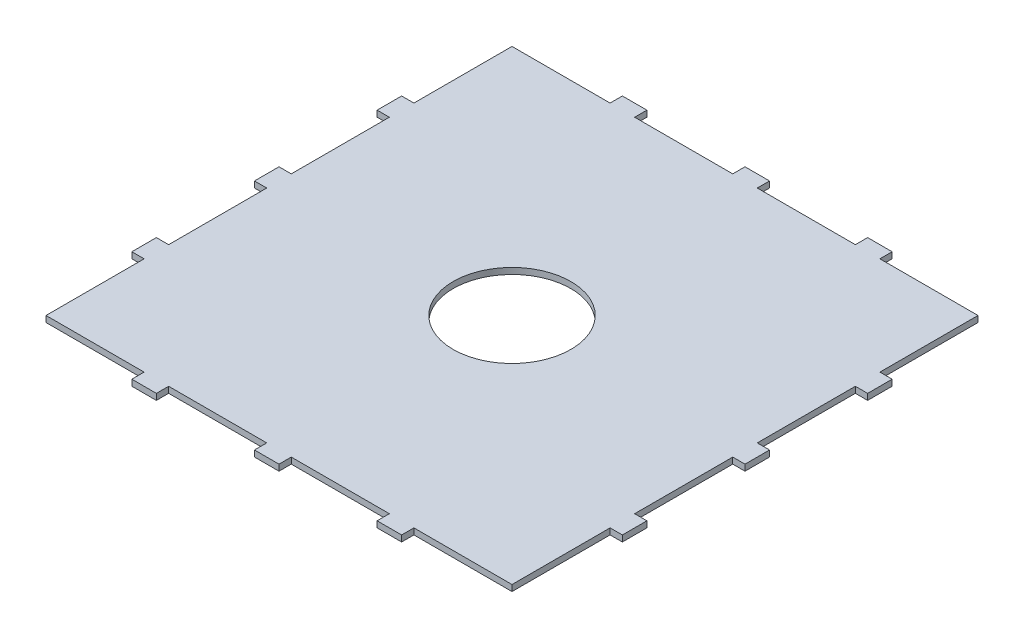
SolidWorks part; units mm, degrees
material "6061 Alloy"
ref_plane "Front Plane" through (0, 0, 0) normal (0, 0, 1) x (1, 0, 0)
ref_plane "Top Plane" through (0, 0, 0) normal (0, 1, 0) x (1, 0, 0)
ref_plane "Right Plane" through (0, 0, 0) normal (1, 0, 0) x (0, 0, -1)
sketch "Sketch1" plane through (0, 0, 0) normal (0, 1, 0) x (1, 0, 0)
  line L0 (0, 63.5) -> (0, -63.5) construction
  line L1 (63.5, -63.5) -> (-63.5, -63.5) construction
  line L2 (63.5, -63.5) -> (63.5, 63.5) construction
  line L3 (63.5, 63.5) -> (-63.5, 63.5) construction
  line L4 (-63.5, -63.5) -> (-63.5, 63.5) construction
  line L5 (63.5, -63.5) -> (-63.5, 63.5) construction
  line L6 (63.5, 63.5) -> (-63.5, -63.5) construction
  line L7 (-63.5, 0) -> (63.5, 0) construction
  line L8 (3.175, 63.5) -> (-3.175, 63.5)
  line L9 (-3.175, 63.5) -> (-3.175, 60.325)
  line L10 (-3.175, 60.325) -> (-28.575, 60.325)
  line L11 (-28.575, 60.325) -> (-28.575, 63.5)
  line L12 (-28.575, 63.5) -> (-34.925, 63.5)
  line L13 (-34.925, 63.5) -> (-34.925, 60.325)
  line L14 (-34.925, 60.325) -> (-60.325, 60.325)
  line L15 (-60.325, 60.325) -> (-60.325, 34.925)
  line L16 (-60.325, 34.925) -> (-63.5, 34.925)
  line L17 (-63.5, 34.925) -> (-63.5, 28.575)
  line L18 (-63.5, 28.575) -> (-60.325, 28.575)
  line L19 (-60.325, 28.575) -> (-60.325, 3.175)
  line L20 (-60.325, 3.175) -> (-63.5, 3.175)
  line L21 (-63.5, 3.175) -> (-63.5, -3.175)
  line L22 (-63.5, -28.575) -> (-60.325, -28.575)
  line L23 (-63.5, -34.925) -> (-63.5, -28.575)
  line L24 (-60.325, -34.925) -> (-63.5, -34.925)
  line L25 (-60.325, -60.325) -> (-60.325, -34.925)
  line L26 (-34.925, -60.325) -> (-60.325, -60.325)
  line L27 (-34.925, -63.5) -> (-34.925, -60.325)
  line L28 (-28.575, -63.5) -> (-34.925, -63.5)
  line L29 (-28.575, -60.325) -> (-28.575, -63.5)
  line L30 (-3.175, -60.325) -> (-28.575, -60.325)
  line L31 (-3.175, -63.5) -> (-3.175, -60.325)
  line L32 (3.175, -63.5) -> (-3.175, -63.5)
  line L33 (-60.325, -28.575) -> (-60.325, -3.175)
  line L34 (-60.325, -3.175) -> (-63.5, -3.175)
  line L35 (63.5, -63.5) -> (63.5, 63.5) construction
  line L36 (60.325, -3.175) -> (63.5, -3.175)
  line L37 (60.325, -28.575) -> (60.325, -3.175)
  line L38 (3.175, -63.5) -> (3.175, -60.325)
  line L39 (3.175, -60.325) -> (28.575, -60.325)
  line L40 (28.575, -60.325) -> (28.575, -63.5)
  line L41 (28.575, -63.5) -> (34.925, -63.5)
  line L42 (34.925, -63.5) -> (34.925, -60.325)
  line L43 (34.925, -60.325) -> (60.325, -60.325)
  line L44 (60.325, -60.325) -> (60.325, -34.925)
  line L45 (60.325, -34.925) -> (63.5, -34.925)
  line L46 (63.5, -34.925) -> (63.5, -28.575)
  line L47 (63.5, -28.575) -> (60.325, -28.575)
  line L48 (63.5, -3.175) -> (63.5, 3.175)
  line L49 (60.325, 3.175) -> (63.5, 3.175)
  line L50 (60.325, 28.575) -> (60.325, 3.175)
  line L51 (63.5, 28.575) -> (60.325, 28.575)
  line L52 (63.5, 34.925) -> (63.5, 28.575)
  line L53 (60.325, 34.925) -> (63.5, 34.925)
  line L54 (60.325, 60.325) -> (60.325, 34.925)
  line L55 (34.925, 60.325) -> (60.325, 60.325)
  line L56 (34.925, 63.5) -> (34.925, 60.325)
  line L57 (28.575, 63.5) -> (34.925, 63.5)
  line L58 (28.575, 60.325) -> (28.575, 63.5)
  line L59 (3.175, 60.325) -> (28.575, 60.325)
  line L60 (3.175, 63.5) -> (3.175, 60.325)
  circle A0 centre (0, 0) radius 15.24
  point P0 (0, 0)
  dimension "D5" = 30.48
  dimension "D1" = 127
  dimension "D2" = 6.35
  dimension "D3" = 3.175
  dimension "D4" = 3.175
extrude "Boss-Extrude1" add sketch "Sketch1" along normal blind 1.5875
